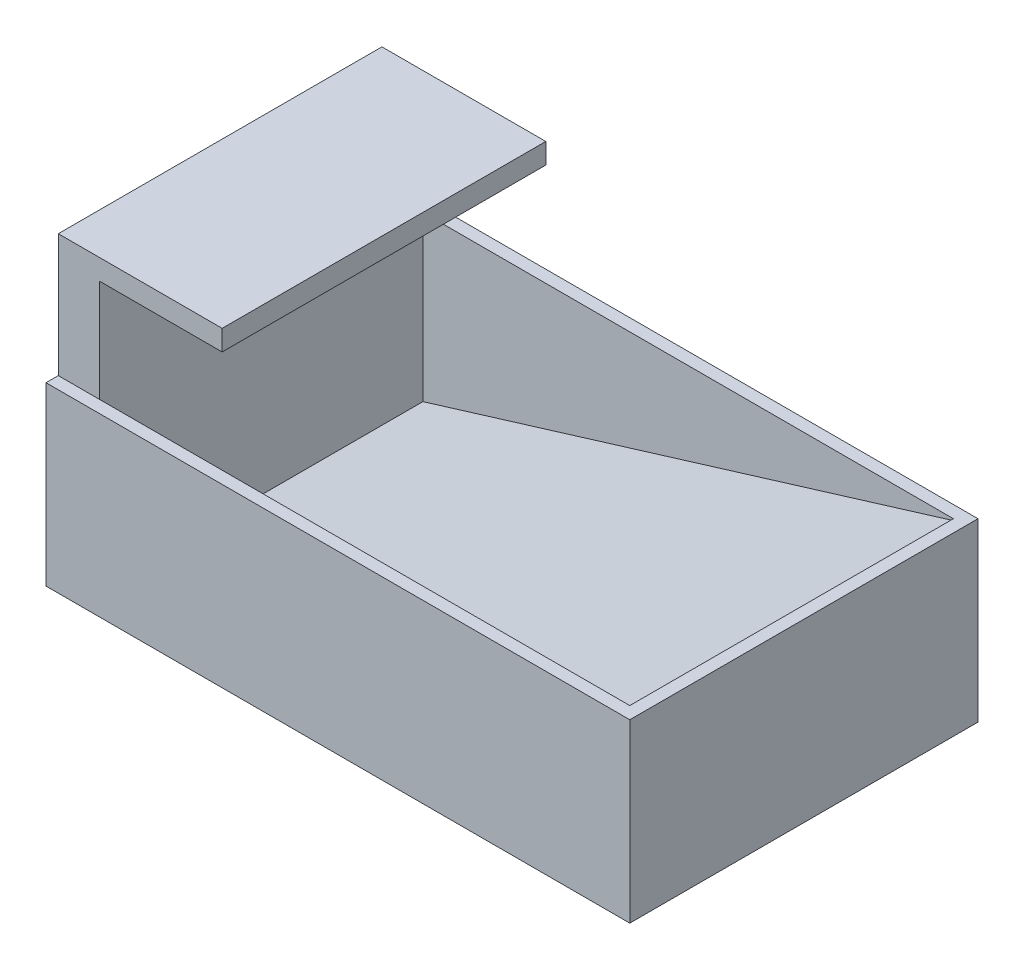
SolidWorks part; units mm, degrees
ref_plane "Front Plane" through (0, 0, 0) normal (0, 0, 1) x (1, 0, 0)
ref_plane "Top Plane" through (0, 0, 0) normal (0, 1, 0) x (1, 0, 0)
ref_plane "Right Plane" through (0, 0, 0) normal (1, 0, 0) x (0, 0, -1)
sketch "Sketch1" plane through (0, 0, 0) normal (0, 1, 0) x (1, 0, 0)
  line L1 (0, 0) -> (142.5, 0)
  line L2 (0, 0) -> (0, 85)
  line L3 (0, 85) -> (142.5, 85)
  line L4 (142.5, 0) -> (142.5, 85)
  dimension "D1" = 142.5
  dimension "D2" = 85
extrude "Boss-Extrude1" add sketch "Sketch1" along normal blind 43
sketch "Sketch2" plane through (0, 43, 0) normal (0, 1, 0) x (1, 0, 0)
  line L0 (142.5, 85) -> (0, 85) construction
  line L1 (10, 3) -> (139.5, 3)
  line L2 (10, 3) -> (10, 82)
  line L3 (10, 82) -> (139.5, 82)
  line L4 (139.5, 3) -> (139.5, 82)
  line L5 (0, 85) -> (0, 0) construction
  line L6 (0, 0) -> (142.5, 0) construction
  line L7 (142.5, 0) -> (142.5, 85) construction
  dimension "D1" = 3
  dimension "D2" = 10
  dimension "D3" = 3
  dimension "D4" = 3
extrude "Cut-Extrude1" cut sketch "Sketch2" against normal blind 40
ref_plane "Plane1" through (0, 0, -3) normal (0, 0, 1) x (1, 0, 0)
sketch "Sketch5" plane through (0, 0, -3) normal (0, 0, 1) x (1, 0, 0)
  line L0 (10, 43) -> (10, 68)
  line L1 (10, 68) -> (40, 68)
  line L2 (40, 68) -> (40, 73)
  line L3 (40, 73) -> (0, 73)
  line L4 (0, 73) -> (0, 43)
  line L5 (0, 43) -> (10, 43)
  dimension "D1" = 30
  dimension "D2" = 25
  dimension "D3" = 40
extrude "Boss-Extrude2" add sketch "Sketch5" against normal blind 79
sketch "Sketch6" plane through (0, 0, -3) normal (0, 0, 1) x (1, 0, 0)
  line L0 (10, 3) -> (139.5, 42.5921)
  line L1 (139.5, 3) -> (139.5, 43) construction
  line L2 (139.5, 42.5921) -> (139.5, 3)
  line L3 (10, 3) -> (139.5, 3) construction
  line L4 (139.5, 3) -> (10, 3)
  dimension "D1" = 17
extrude "Boss-Extrude3" add sketch "Sketch6" against normal blind 79
